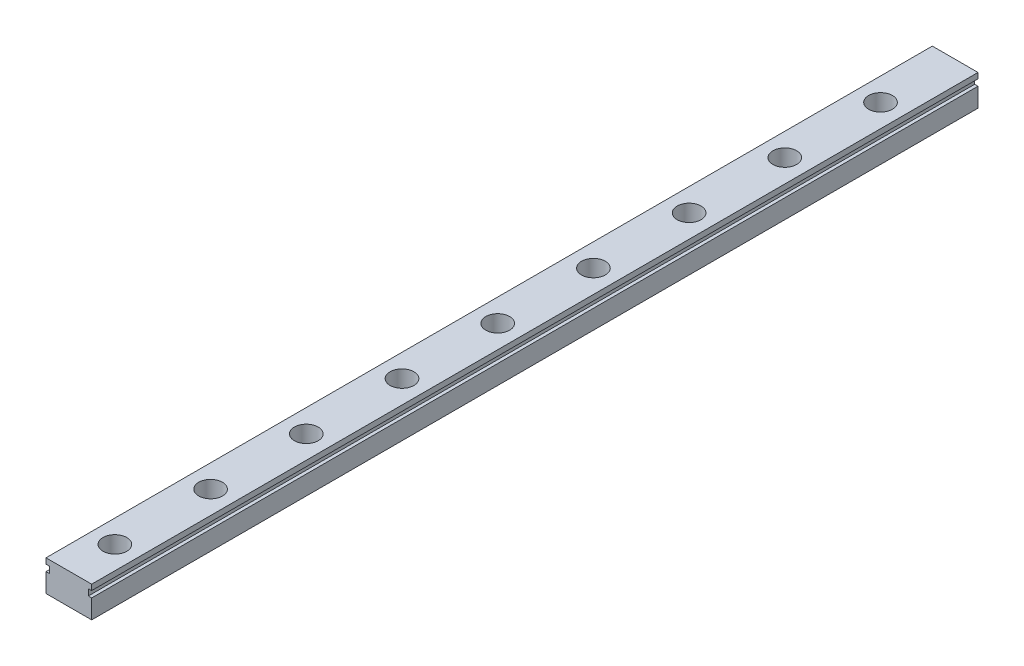
SolidWorks part; units mm, degrees
ref_plane "Front Plane" through (0, 0, 0) normal (0, 0, 1) x (1, 0, 0)
ref_plane "Top Plane" through (0, 0, 0) normal (0, 1, 0) x (1, 0, 0)
ref_plane "Right Plane" through (0, 0, 0) normal (1, 0, 0) x (0, 0, -1)
sketch "Sketch1" plane through (0, 0, 0) normal (0, 0, 1) x (1, 0, 0)
  line L1 (-5.75, -3.9) -> (5.75, -3.9)
  line L2 (-5.75, -3.9) -> (-5.75, 3.9)
  line L3 (-5.75, 3.9) -> (5.75, 3.9)
  line L4 (5.75, -3.9) -> (5.75, 3.9)
  line L5 (-5.75, -3.9) -> (5.75, 3.9) construction
  line L6 (-5.75, 3.9) -> (5.75, -3.9) construction
  point P0 (0, 0)
  dimension "D1" = 11.5
  dimension "D2" = 7.8
extrude "Boss-Extrude1" add sketch "Sketch1" along normal blind 223.2
sketch "Sketch2" plane through (0, 0, 223.2) normal (0, 0, 1) x (1, 0, 0)
  line L0 (5.75, -3.9) -> (5.75, 3.9) construction
  line L1 (5.75, 2.5) -> (4.9147, 2.5)
  line L2 (5.75, 2.5) -> (5.75, 0.9)
  line L3 (5.75, 0.9) -> (4.9147, 0.9)
  line L4 (4.9147, 2.5) -> (4.9147, 0.9)
  line L5 (5.75, 3.9) -> (-5.75, 3.9) construction
  line L7 (0, -4.29) -> (0, 4.29) construction
  line L8 (-5.75, 0.9) -> (-4.9147, 0.9)
  line L9 (-4.9147, 2.5) -> (-4.9147, 0.9)
  line L10 (-5.75, 2.5) -> (-4.9147, 2.5)
  line L11 (-5.75, 2.5) -> (-5.75, 0.9)
  dimension "D1" = 1.4
  dimension "D2" = 1.6
extrude "Cut-Extrude1" cut sketch "Sketch2" against normal through all
sketch "Sketch3" plane through (0, 3.9, 0) normal (0, 1, 0) x (1, 0, 0)
  line L0 (0, -223.2) -> (0, -215.9183) construction
  line L2 (5.75, -223.2) -> (-5.75, -223.2) construction
  circle A0 centre (0, -211.6) radius 3
  circle A1 centre (0, -187.5) radius 3
  circle A2 centre (0, -163.4) radius 3
  circle A3 centre (0, -139.3) radius 3
  circle A4 centre (0, -115.2) radius 3
  circle A5 centre (0, -91.1) radius 3
  circle A6 centre (0, -67) radius 3
  circle A7 centre (0, -42.9) radius 3
  circle A8 centre (0, -18.8) radius 3
  dimension "D1" = 11.6
  dimension "D2" = 6
  dimension "D3" = 9
extrude "Cut-Extrude2" cut sketch "Sketch3" against normal blind 4.7
sketch "Sketch4" plane through (0, -0.8, 0) normal (0, 1, 0) x (1, 0, 0)
  circle A0 centre (0, -211.6) radius 1.7
  circle A1 centre (0, -187.5) radius 1.7
  circle A2 centre (0, -163.4) radius 1.7
  circle A3 centre (0, -139.3) radius 1.7
  circle A4 centre (0, -115.2) radius 1.7
  circle A5 centre (0, -91.1) radius 1.7
  circle A6 centre (0, -67) radius 1.7
  circle A7 centre (0, -42.9) radius 1.7
  circle A8 centre (0, -18.8) radius 1.7
  dimension "D1" = 3.4
  dimension "D2" = 9
extrude "Cut-Extrude3" cut sketch "Sketch4" against normal through all
